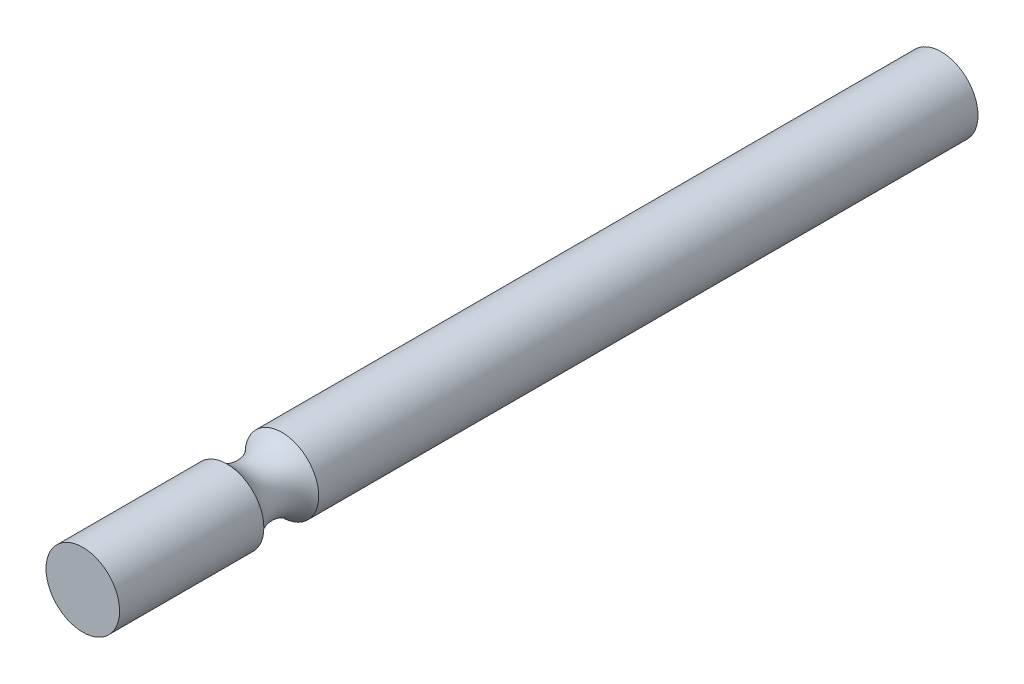
SolidWorks part; units mm, degrees
ref_plane "前视基准面" through (0, 0, 0) normal (0, 0, 1) x (1, 0, 0)
ref_plane "上视基准面" through (0, 0, 0) normal (0, 1, 0) x (1, 0, 0)
ref_plane "右视基准面" through (0, 0, 0) normal (1, 0, 0) x (0, 0, -1)
sketch "草图1" plane through (0, 0, 0) normal (0, 0, 1) x (1, 0, 0)
  circle A0 centre (0, 0) radius 1.5
  dimension "D1" = 3
extrude "凸台-拉伸1" add sketch "草图1" along normal blind 35
cosmetic thread "装饰螺纹线1" parameters "D1"=25, "D2"=2.5
sketch "草图2" plane through (0, 0, 0) normal (1, 0, 0) x (0, 0, -1)
  line L1 (-35, 1.5) -> (-35, -1.5) construction
  line L2 (-35, 0) -> (-16.0954, 0) construction
  line L3 (-29.5, 2.5) -> (-26.5, 2.5)
  arc A0 (-29.5, 2.5) -> (-26.5, 2.5) centre (-28, 2.5) ccw
  dimension "D2" = 3
  dimension "D1" = 7
  dimension "D3" = 2.5
revolve "切除-旋转1" cut sketch "草图2" angle 360 about L2
